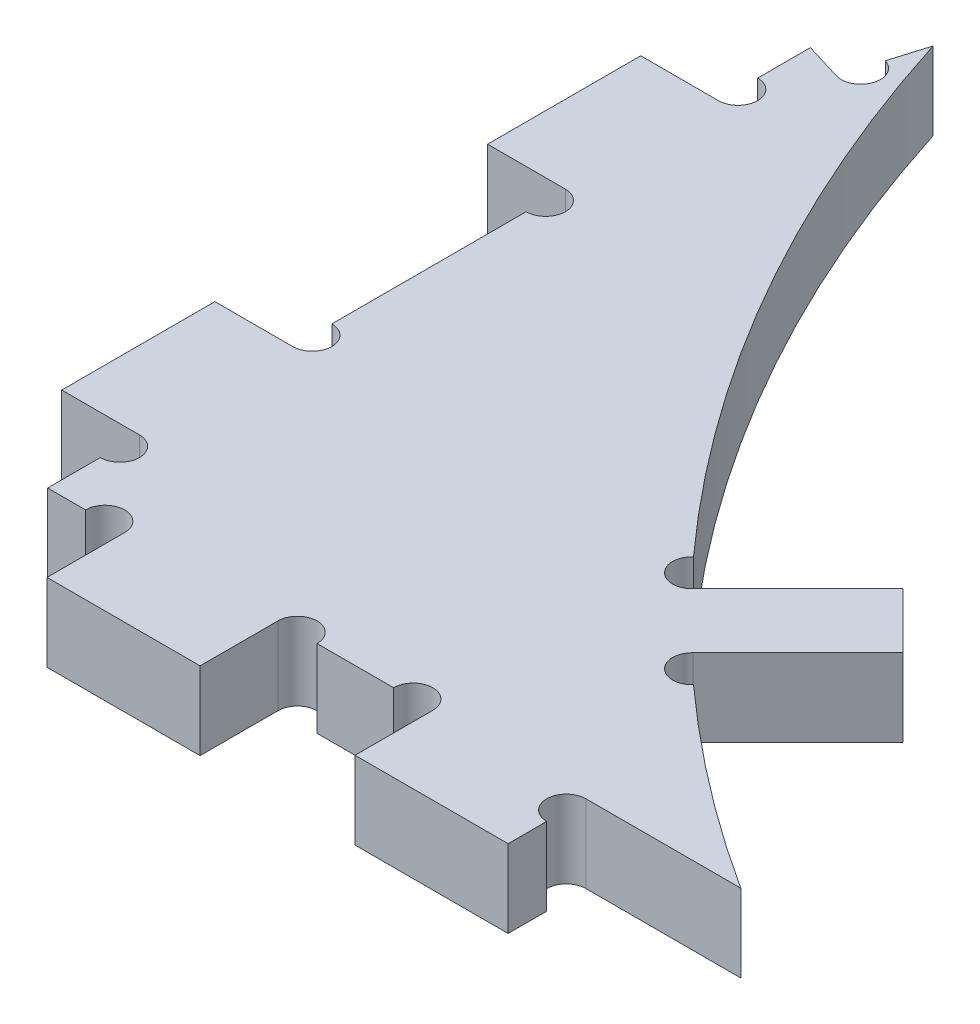
SolidWorks part; units mm, degrees
ref_plane "Front Plane" through (0, 0, 0) normal (0, 0, 1) x (1, 0, 0)
ref_plane "Top Plane" through (0, 0, 0) normal (0, 1, 0) x (1, 0, 0)
ref_plane "Right Plane" through (0, 0, 0) normal (1, 0, 0) x (0, 0, -1)
sketch "Sketch1" plane through (0, 0, 0) normal (0, 1, 0) x (1, 0, 0)
  line L0 (-134.8694, -210.5) -> (-160.1567, -210.5)
  line L1 (-160.1567, -210.5) -> (-160.1567, -223.2)
  line L2 (-160.1567, -223.2) -> (-185.1567, -223.2)
  line L3 (-185.1567, -223.2) -> (-185.1567, -210.5)
  line L4 (-185.1567, -210.5) -> (-210.4467, -210.5)
  line L5 (-210.4467, -210.5) -> (-210.4467, -223.2)
  line L6 (-210.4467, -223.2) -> (-235.4467, -223.2)
  line L7 (-235.4467, -223.2) -> (-235.4467, -210.5)
  line L8 (-235.4467, -210.5) -> (-248.0367, -210.5)
  line L9 (-248.0367, -210.5) -> (-248.0367, -195.5)
  line L10 (-248.0367, -195.5) -> (-260.7367, -195.5)
  line L11 (-260.7367, -195.5) -> (-260.7367, -170.5)
  line L12 (-260.7367, -170.5) -> (-248.0367, -170.5)
  line L13 (-248.0367, -170.5) -> (-248.0367, -125.9748)
  line L14 (-248.0367, -125.9748) -> (-260.7367, -125.9748)
  line L15 (-260.7367, -125.9748) -> (-260.7367, -100.9748)
  line L16 (-260.7367, -100.9748) -> (-248.0367, -100.9748)
  line L17 (-248.0367, -100.9748) -> (-248.0367, -85.9748)
  line L18 (-248.0367, -85.9748) -> (-241.9324, -87.8303)
  line L19 (-241.9324, -87.8303) -> (-238.2541, -75.7295)
  line L20 (-181.2442, -172.1933) -> (-163.9781, -154.9271)
  line L21 (-163.9781, -154.9271) -> (-154.9271, -163.9781)
  line L22 (-154.9271, -163.9781) -> (-172.1933, -181.2442)
  line L23 (0, 0) -> (-238.2541, -75.7295) construction
  line L24 (0, 0) -> (-159.4526, -159.4526) construction
  line L25 (0, 0) -> (-134.8694, -210.5) construction
  line L26 (0, 0) -> (0, 250) construction
  circle A0 centre (0, 0) radius 250 construction
  arc A1 (-238.2541, -75.7295) -> (-181.2442, -172.1933) centre (0, 0) ccw
  arc A2 (-172.1933, -181.2442) -> (-134.8694, -210.5) centre (0, 0) ccw
  dimension "D1" = 500
  dimension "D2" = 73.092
  dimension "D3" = 135
  dimension "D4" = 27.367
  dimension "D6" = 12.8
  dimension "D7" = 24.4181
  dimension "D8" = 12.7
  dimension "D9" = 12.7
  dimension "D10" = 25
  dimension "D11" = 25
  dimension "D12" = 15
  dimension "D13" = 12.59
  dimension "D14" = 25.29
  dimension "D15" = 44.5252
  dimension "D16" = 25.2873
  dimension "D17" = 124.5252
  dimension "D18" = 12.6475
extrude "Boss-Extrude1" add sketch "Sketch1" along normal blind 12.7
sketch "Sketch2" plane through (0, 12.7, 0) normal (0, 1, 0) x (1, 0, 0)
  line L0 (-248.0367, -125.9748) -> (-248.0367, -170.5) construction
  line L1 (-248.0367, -85.9748) -> (-248.0367, -100.9748) construction
  line L2 (-248.0367, -195.5) -> (-248.0367, -210.5) construction
  line L3 (-248.0367, -210.5) -> (-235.4467, -210.5) construction
  line L4 (-210.4467, -210.5) -> (-185.1567, -210.5) construction
  line L5 (-160.1567, -223.2) -> (-160.1567, -210.5) construction
  line L6 (-238.2541, -75.7295) -> (-241.9324, -87.8303) construction
  circle A0 centre (-248.0367, -129.1748) radius 3.2
  circle A1 centre (-248.0367, -97.7748) radius 3.2
  circle A2 centre (-248.0367, -167.3) radius 3.2
  circle A3 centre (-248.0367, -198.7) radius 3.2
  circle A4 centre (-238.6467, -210.5) radius 3.2
  circle A5 centre (-207.2467, -210.5) radius 3.2
  circle A6 centre (-188.3567, -210.5) radius 3.2
  circle A7 centre (-160.1567, -213.7) radius 3.2
  circle A8 centre (-183.4334, -169.8593) radius 3.2
  arc A9 (-238.2541, -75.7295) -> (-181.2442, -172.1933) centre (0, 0) ccw construction
  circle A10 centre (-169.8593, -183.4334) radius 3.2
  arc A11 (-172.1933, -181.2442) -> (-134.8694, -210.5) centre (0, 0) ccw construction
  circle A12 centre (-241.0018, -84.7686) radius 3.2
  dimension "D1" = 6.4
extrude "Cut-Extrude1" cut sketch "Sketch2" against normal through all
